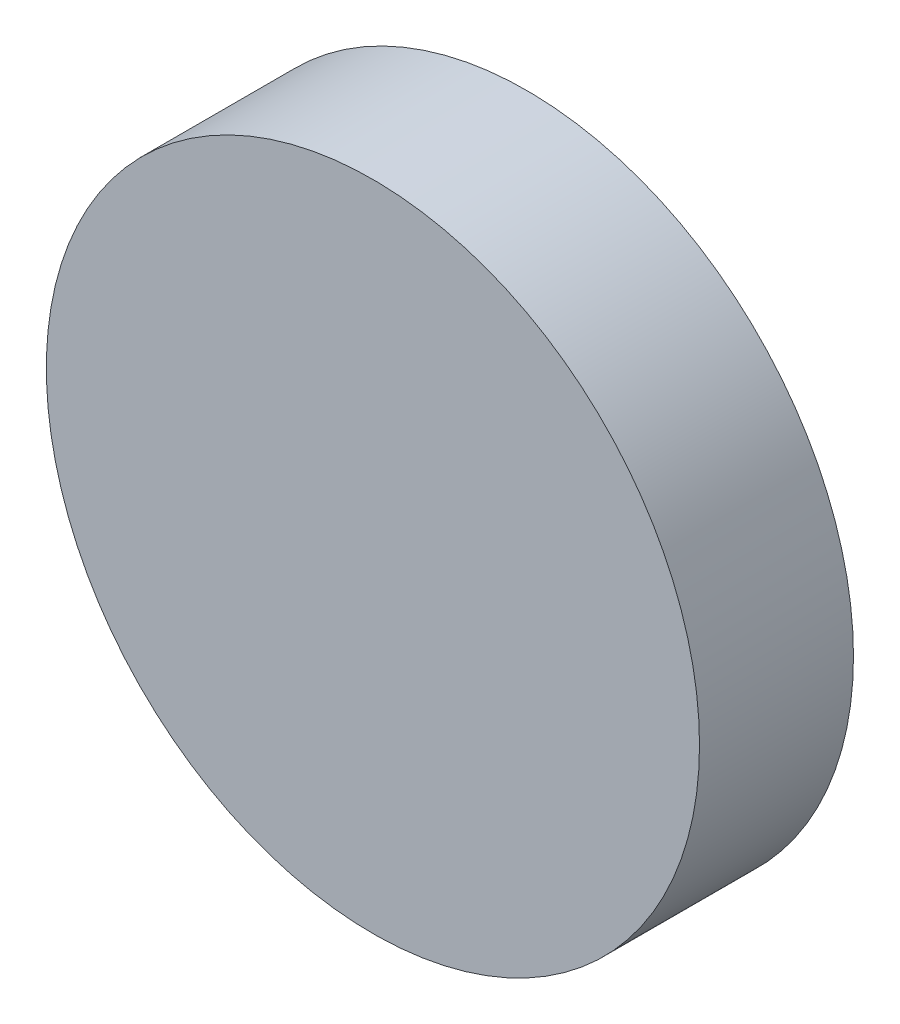
SolidWorks part; units mm, degrees
ref_plane "Ön Düzlem" through (0, 0, 0) normal (0, 0, 1) x (1, 0, 0)
ref_plane "Üst Düzlem" through (0, 0, 0) normal (0, 1, 0) x (1, 0, 0)
ref_plane "Sağ Düzlem" through (0, 0, 0) normal (1, 0, 0) x (0, 0, -1)
sketch "Sketch1" plane through (0, 0, 0) normal (0, 0, 1) x (1, 0, 0)
  circle A0 centre (0, 0) radius 70
  dimension "D1" = 140
extrude "Boss-Extrude1" add sketch "Sketch1" along normal blind 33
